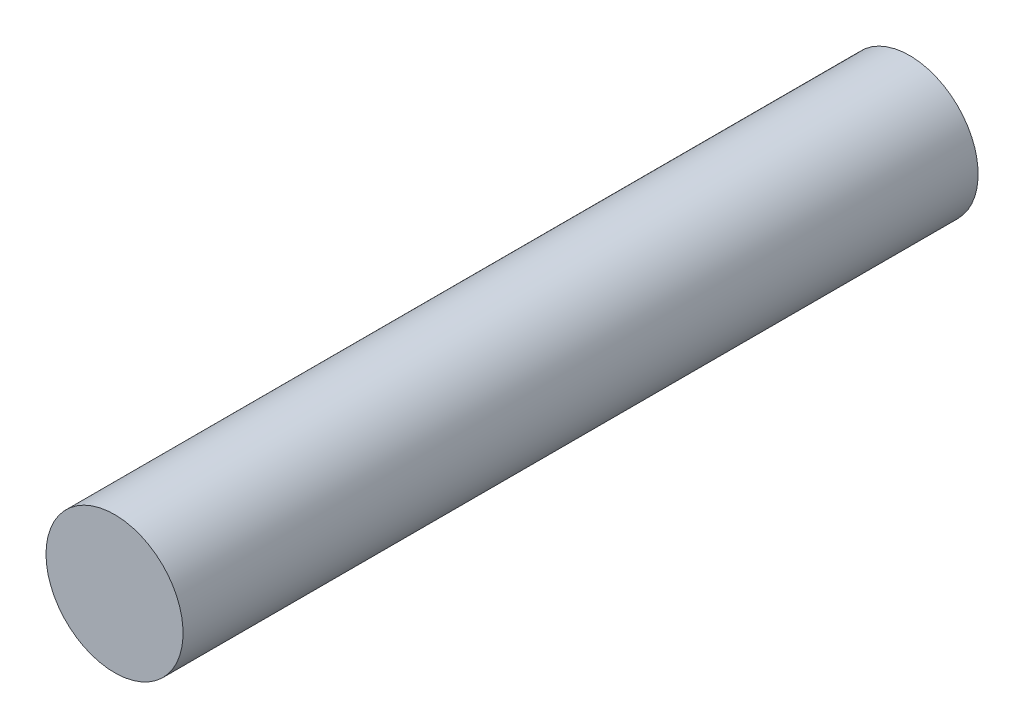
SolidWorks part; units mm, degrees
ref_plane "Front Plane" through (0, 0, 0) normal (0, 0, 1) x (1, 0, 0)
ref_plane "Top Plane" through (0, 0, 0) normal (0, 1, 0) x (1, 0, 0)
ref_plane "Right Plane" through (0, 0, 0) normal (1, 0, 0) x (0, 0, -1)
sketch "Sketch1" plane through (0, 0, 0) normal (0, 0, 1) x (1, 0, 0)
  circle A0 centre (0, 0) radius 5
  dimension "D1" = 10
extrude "Boss-Extrude1" add sketch "Sketch1" along normal blind 58
